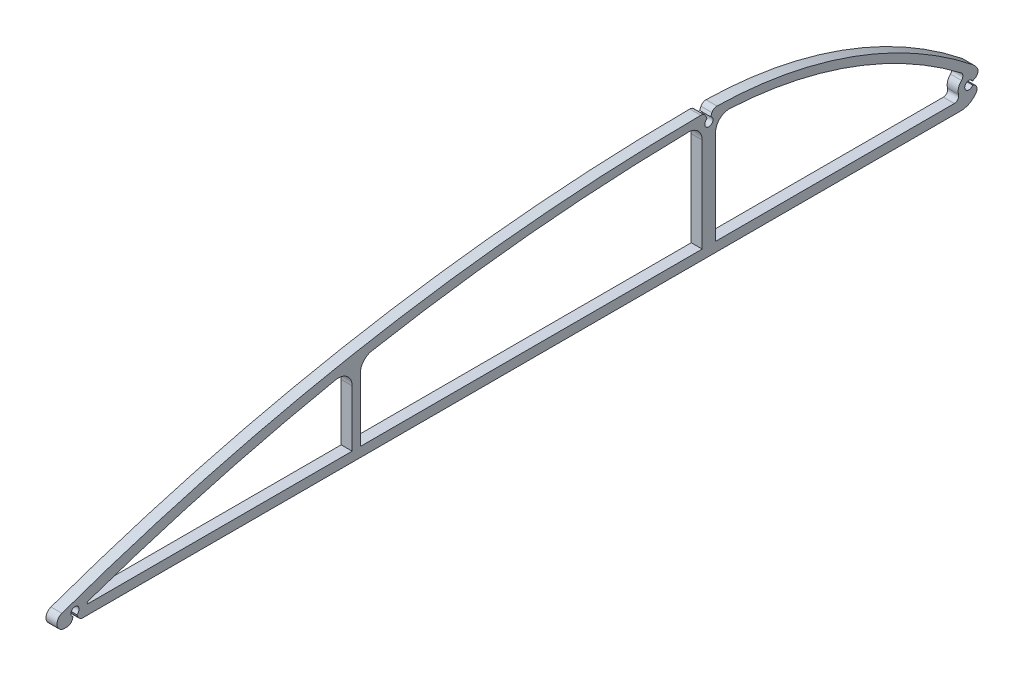
SolidWorks part; units mm, degrees
other "Marquage1"
sketch "Esquisse8" plane through (8, 0, -172.8424) normal (1, 0, 0) x (0, 0, -1)
other "Marquage2"
sketch "Esquisse10" plane through (-6, 20, -172.8424) normal (-0.8365, 0.2588, -0.483) x (-0.5, 0, 0.866)
other "Marquage3"
sketch "Esquisse11" plane through (0, 0, 0) normal (-0.0501, -0.1345, 0.9896) x (0.9942, 0.0873, 0.0622)
ref_plane "Plan de face" through (0, 0, 0) normal (0, 0, 1) x (1, 0, 0)
ref_plane "Plan de dessus" through (0, 0, 0) normal (0, 1, 0) x (1, 0, 0)
ref_plane "Plan de droite" through (0, 0, 0) normal (1, 0, 0) x (0, 0, -1)
sketch "Esquisse2" plane through (0, 0, 0) normal (1, 0, 0) x (0, 0, -1)
  line L0 (0, 0) -> (170.8732, 0)
  arc A1 (173.0499, 6.2408) -> (125, 23) centre (125, -54.2609) ccw
  arc A3 (170.8732, 0) -> (173.0499, 6.2408) centre (170.8732, 3.5) ccw
  arc A4 (125, 23) -> (0, 0) centre (125, -328.1739) ccw
  point P10 (180, 0)
  dimension "D1" = 180
  dimension "D2" = 3.5
  dimension "D3" = 23
  dimension "D4" = 55
extrude "Boss.-Extru.1" add sketch "Esquisse2" along normal blind 2
fillet "Congé2" radius 1.35 1 edges at (1, 0, 0)
sketch "Esquisse4" plane through (2, 0, 0) normal (1, 0, 0) x (0, 0, -1)
  line L0 (9.5, 0) -> (9.5, 3.4627) construction
  line L1 (0, 0) -> (9.5, 1.7314) construction
  line L10 (174.369, 3.3283) -> (172.369, 3.3283) construction
  line L11 (7.5659, 0) -> (170.8732, 0) construction
  line L12 (125, 21.2) -> (125, 23) construction
  line L14 (126.3989, 24.2) -> (125, 21.2)
  line L15 (125, 21.2) -> (123.6011, 24.2)
  line L17 (123.6011, 24.2) -> (126.3989, 24.2)
  line L18 (172.369, 3.3283) -> (175.369, 4.7273)
  line L19 (175.369, 4.7273) -> (175.369, 1.9294)
  line L20 (175.369, 1.9294) -> (172.369, 3.3283)
  line L21 (9.5, 1.7314) -> (8.1011, -1.2686)
  line L22 (8.1011, -1.2686) -> (10.8989, -1.2686)
  line L23 (10.8989, -1.2686) -> (9.5, 1.7314)
  circle A6 centre (125, 21.2) radius 0.75
  circle A12 centre (172.369, 3.3283) radius 0.75
  arc A13 (170.8732, 0) -> (173.0499, 6.2408) centre (170.8732, 3.5) ccw construction
  circle A15 centre (9.5, 1.7314) radius 0.75
  arc A16 (125, 23) -> (7.1127, 2.6217) centre (125, -328.1739) ccw construction
  arc A17 (173.0499, 6.2408) -> (125, 23) centre (125, -54.2609) ccw construction
  point P18 (125, 24.2)
  point P24 (9.5, -1.2686)
  point P28 (175.369, 3.3283)
  point P37 (0, 0)
  point P38 (0, 0)
  point P39 (120.8427, 21.2)
  arc M5 (125, 23) -> (7.1127, 2.6217) centre (125, -328.1739) ccw
  line M6 (7.5659, 0) -> (170.8732, 0)
  arc M7 (170.8732, 0) -> (173.0499, 6.2408) centre (170.8732, 3.5) ccw
  arc M8 (173.0499, 6.2408) -> (125, 23) centre (125, -54.2609) ccw
  dimension "D1" = 1.5
  dimension "D2" = 1.5
  dimension "D7" = 1.5
  dimension "D9" = 3
  dimension "D10" = 50
  dimension "D11" = 3
  dimension "D12" = 50
  dimension "D3" = 1.8
  dimension "D4" = 9.5
  dimension "D5" = 3
  dimension "D6" = 2
  dimension "D8" = 50
extrude "Enlèv. mat.-Extru.2" cut sketch "Esquisse4" against normal through all contours L15 A6 L14 | L14 A6 L15 | A12 | A15 | A6 L14 L15 M8 M5 | L17 L15 L14 M5 M8 | A12 L20 L18 M7 | L20 A12 L18 | L20 L19 L18 M7 | L21 A15 L23 | A15 L21 L23 M6 | L22 L23 L21 M6
fillet "Congé5" radius 1 6 edges at (1, 0, -10.3074) (1, 0, -8.6926) (1, 2.4665, -174.2171) (1, 4.2273, -174.2968) (1, 22.999, -124.1611) (1, 22.9955, -125.8372)
sketch "Esquisse9" plane through (0, 0, 0) normal (1, 0, 0) x (0, 0, -1)
  line L26 (126.214, 1.7612) -> (171.2085, 1.7612)
  line L36 (11.7498, 1.7612) -> (60, 1.7612)
  line L40 (61.5, 1.7612) -> (123.786, 1.7612)
  line L42 (60, 1.7612) -> (60, 15.1133)
  line L44 (61.5, 1.7612) -> (61.5, 15.4008)
  line L45 (123.786, 21.4979) -> (123.786, 1.7612)
  line L46 (126.214, 21.4979) -> (126.214, 1.7612)
  line L47 (10.9444, 0) -> (170.8732, 0) construction
  arc A20 (60, 15.1133) -> (11.7185, 2.1065) centre (126.566, -328.0971) ccw
  circle A21 centre (125, 21.2) radius 0.75 construction
  circle A22 centre (9.5, 1.7314) radius 0.75 construction
  arc A23 (173.0499, 6.2408) -> (126.4891, 22.9856) centre (125, -54.2609) ccw construction
  arc A25 (171.9257, 5.2273) -> (171.2085, 1.7612) centre (172.369, 3.3283) ccw
  circle A26 centre (172.369, 3.3283) radius 0.75 construction
  arc A29 (123.5208, 22.9969) -> (7.1127, 2.6217) centre (125, -328.1739) ccw construction
  arc A42 (171.9257, 5.2273) -> (126.214, 21.4979) centre (125, -54.2609) ccw
  arc A43 (123.786, 21.4979) -> (61.5, 15.4008) centre (126.566, -328.0971) ccw
  arc A54 (11.7498, 1.7612) -> (11.7185, 2.1065) centre (9.5, 1.7314) ccw
  dimension "D2" = 1.25
  dimension "D3" = 1.2
  dimension "D5" = 1.25
  dimension "D4" = 1.5
  dimension "D6" = 1.5
  dimension "D7" = 60
  dimension "D8" = 1.7612
extrude "Enlèv. mat.-Extru.3" cut sketch "Esquisse9" along normal blind 4
fillet "Congé3" radius 2.5 4 edges at (1, 21.4979, -126.214) (1, 21.4979, -123.786) (1, 15.1133, -60) (1, 15.4008, -61.5)
fillet "Congé4" radius 0.8 2 edges at (1, 1.7612, -171.2085) (1, 5.2273, -171.9257)
